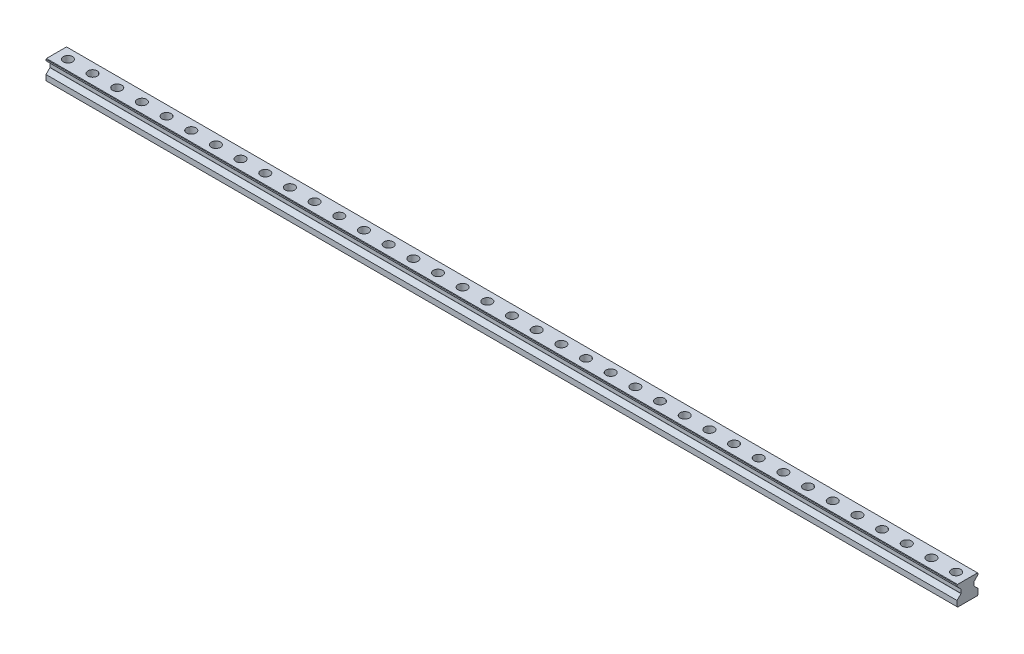
SolidWorks part; units mm, degrees
material "Low Carbon Steel"
ref_plane "Front Plane" through (0, 0, 0) normal (0, 0, 1) x (1, 0, 0)
ref_plane "Top Plane" through (0, 0, 0) normal (0, 1, 0) x (1, 0, 0)
ref_plane "Right Plane" through (0, 0, 0) normal (1, 0, 0) x (0, 0, -1)
sketch "Sketch2" plane through (0, 0, 0) normal (1, 0, 0) x (0, 0, -1)
  line L0 (10.6172, 22.7591) -> (17, 29.1419)
  line L1 (17, 29.1419) -> (17, 31.25)
  line L2 (17, 31.25) -> (16.25, 32)
  line L3 (16.25, 32) -> (-16.25, 32)
  line L4 (-16.25, 32) -> (-17, 31.25)
  line L5 (-17, 31.25) -> (-17, 29.1419)
  line L6 (-17, 29.1419) -> (-10.6172, 22.7591)
  line L7 (-10.5, 22.4762) -> (-10.5, 16.5238)
  line L8 (-10.6172, 16.2409) -> (-17, 9.8581)
  line L9 (-17, 9.8581) -> (-17, 1)
  line L10 (-17, 1) -> (-16, 0)
  line L11 (-16, 0) -> (16, 0)
  line L12 (16, 0) -> (17, 1)
  line L13 (17, 1) -> (17, 9.8581)
  line L14 (17, 9.8581) -> (10.6172, 16.2409)
  line L15 (10.5, 16.5238) -> (10.5, 22.4762)
  arc A0 (10.6172, 22.7591) -> (10.5, 22.4762) centre (10.9, 22.4762) ccw
  arc A1 (-10.5, 22.4762) -> (-10.6172, 22.7591) centre (-10.9, 22.4762) ccw
  arc A2 (-10.6172, 16.2409) -> (-10.5, 16.5238) centre (-10.9, 16.5238) ccw
  arc A3 (10.5, 16.5238) -> (10.6172, 16.2409) centre (10.9, 16.5238) ccw
extrude "Boss-Extrude2" add sketch "Sketch2" along normal mid plane 1477
hole_wizard "CBORE for M8 SHCS1" positions "Sketch4" profile "Sketch3" counterbore size "M8" standard "ANSI Metric" end condition through all
sketch "Sketch4" plane through (0, 32, 0) normal (0, 1, 0) x (-1, 0, 0)
  line L0 (-738.5, -16.25) -> (-738.5, 16.25) construction
  point P0 (-720, 0)
  point P4 (-738.5, 0)
  dimension "D1" = 18.5
sketch "Sketch3" plane through (720, 32, 0) normal (1, 0, 0) x (0, 0, 1)
  line L0 (0, 0) -> (0, 32)
  line L1 (0, 32) -> (4.5, 32)
  line L3 (4.5, 32) -> (4.5, 17)
  line L4 (4.5, 17) -> (7.5, 17)
  line L5 (7.5, 17) -> (7.5, 0)
  line L7 (7.5, 0) -> (0, 0)
  line L11 (0, -6.35) -> (0, 107.95) construction
  dimension "Thru Hole Dia." = 9
  dimension "Thru Hole Depth" = 32
  dimension "C'Bore Dia." = 15
  dimension "C'Bore Depth" = 17
pattern_linear "LPattern1" count 37 spacing 40 along (-1, 0, 0) of "CBORE for M8 SHCS1"
other "Freeze***"
